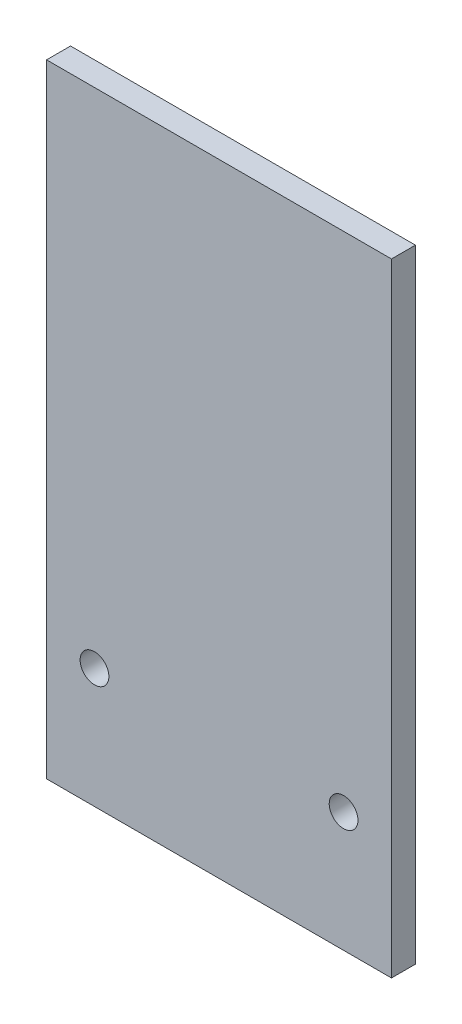
SolidWorks part; units mm, degrees
ref_plane "Front Plane" through (0, 0, 0) normal (0, 0, 1) x (1, 0, 0)
ref_plane "Top Plane" through (0, 0, 0) normal (0, 1, 0) x (1, 0, 0)
ref_plane "Right Plane" through (0, 0, 0) normal (1, 0, 0) x (0, 0, -1)
sketch "Sketch1" plane through (0, 0, 0) normal (0, 0, 1) x (1, 0, 0)
  line L1 (-36, 65) -> (36, 65)
  line L2 (-36, 65) -> (-36, -65)
  line L3 (-36, -65) -> (36, -65)
  line L4 (36, 65) -> (36, -65)
  line L5 (-36, 65) -> (36, -65) construction
  line L6 (-36, -65) -> (36, 65) construction
  point P0 (0, 0)
  dimension "D1" = 130
  dimension "D2" = 72
extrude "Boss-Extrude1" add sketch "Sketch1" along normal blind 5
sketch "Sketch2" plane through (0, 0, 5) normal (0, 0, 1) x (1, 0, 0)
  line L0 (0, 0) -> (0, -65) construction
  line L1 (-36, -65) -> (36, -65) construction
  circle A0 centre (-26, -40) radius 3
  circle A1 centre (26, -40) radius 3
  point P7 (0, 0)
  dimension "D1" = 6
  dimension "D2" = 25
  dimension "28" = 26
extrude "Cut-Extrude1" cut sketch "Sketch2" against normal blind 5
